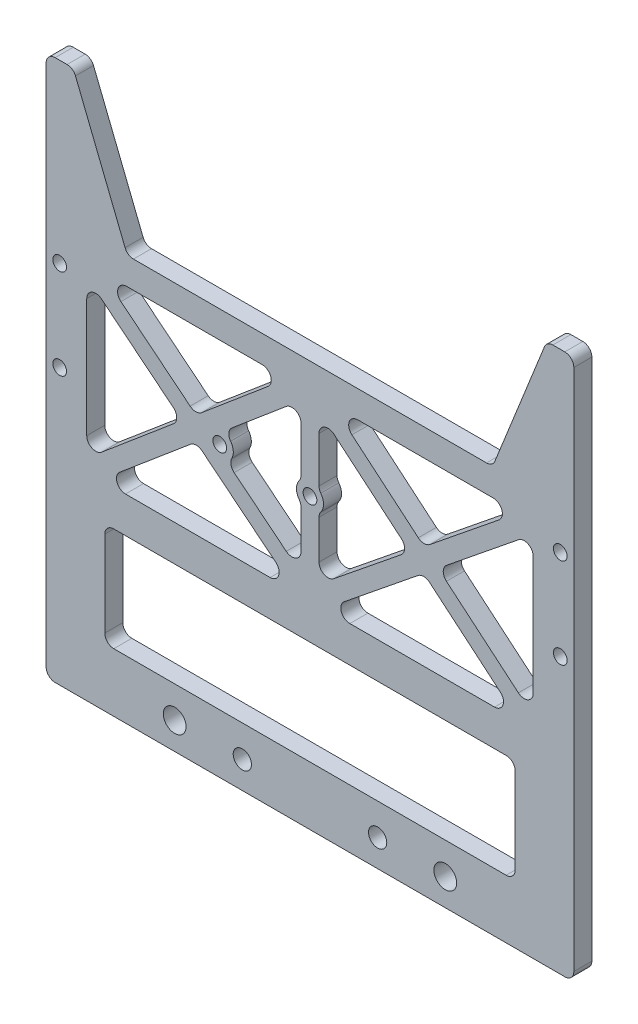
SolidWorks part; units mm, degrees
material "Thornel Mat VMA"
ref_plane "前视基准面" through (0, 0, 0) normal (0, 0, 1) x (1, 0, 0)
ref_plane "上视基准面" through (0, 0, 0) normal (0, 1, 0) x (1, 0, 0)
ref_plane "右视基准面" through (0, 0, 0) normal (1, 0, 0) x (0, 0, -1)
other "Configuration Table"
sketch "草图1" plane through (0, 0, 0) normal (0, 0, 1) x (1, 0, 0)
  line L1 (-58.5, -60) -> (58.5, -60)
  line L2 (-58.5, -60) -> (-58.5, 60)
  line L3 (-58.5, 60) -> (58.5, 60)
  line L4 (58.5, -60) -> (58.5, 60)
  line L5 (-58.5, -60) -> (58.5, 60) construction
  line L6 (-58.5, 60) -> (58.5, -60) construction
  point P0 (0, 0)
  dimension "D1" = 117
  dimension "D2" = 120
extrude "凸台-拉伸1" add sketch "草图1" along normal blind 4
sketch "草图2" [suppressed] plane through (0, 0, 4) normal (0, 0, 1) x (1, 0, 0)
  line L0 (-43.5, 60) -> (-28.5, 35)
  line L1 (58.5, 60) -> (-58.5, 60) construction
  line L2 (-28.5, 35) -> (28.5, 35)
  line L3 (28.5, 35) -> (43.5, 60)
  line L4 (43.5, 60) -> (-43.5, 60)
  line L5 (0, 60) -> (0, 35) construction
  line L6 (0, 35) -> (0, 0) construction
  line L7 (58.5, -60) -> (58.5, 60) construction
  dimension "D1" = 15
  dimension "D2" = 25
  dimension "D3" = 30
extrude "切除-拉伸1" [suppressed] cut sketch "草图2" against normal blind 10
sketch "草图3" [suppressed] plane through (0, 0, 4) normal (0, 0, 1) x (1, 0, 0)
  line L0 (48.5, -48) -> (48.5, -16.5) construction
  line L1 (-48.5, -16.5) -> (-48.5, -48) construction
  line L2 (48.5, -46) -> (48.5, -21)
  line L3 (-48.5, -21) -> (-48.5, -46)
  line L4 (48.5, -46) -> (-48.5, -46)
  line L5 (48.5, -21) -> (-48.5, -21)
  line L6 (-58.5, -60) -> (58.5, -60) construction
  dimension "D1" = 14
  dimension "D2" = 25
extrude "切除-拉伸2" [suppressed] cut sketch "草图3" against normal blind 10
sketch "草图4" plane through (0, 0, 0) normal (0, 0, -1) x (-1, 0, 0)
  line L0 (45.5, -47) -> (45.5, -24)
  line L1 (45.5, -24) -> (-45.5, -24)
  line L2 (-45.5, -24) -> (-45.5, -47)
  line L3 (-45.5, -47) -> (45.5, -47)
  line L4 (43.5, -45) -> (43.5, -26)
  line L5 (43.5, -26) -> (-43.5, -26)
  line L6 (-43.5, -26) -> (-43.5, -45)
  line L7 (-43.5, -45) -> (43.5, -45)
  line L8 (43.5, -45) -> (43.5, -26) construction
  line L9 (43.5, -26) -> (-43.5, -26) construction
  line L10 (-43.5, -26) -> (-43.5, -45) construction
  line L11 (-43.5, -45) -> (43.5, -45) construction
  dimension "D1" = 0
  dimension "D2" = 2
extrude "切除-拉伸3" cut sketch "草图4" against normal blind 10
sketch "草图5" plane through (0, 0, 4) normal (0, 0, 1) x (1, 0, 0)
  line L0 (-52.5, 60) -> (-40.5, 30)
  line L1 (58.5, 60) -> (-58.5, 60) construction
  line L2 (-40.5, 30) -> (40.5, 30)
  line L3 (40.5, 30) -> (52.5, 60)
  line L4 (52.5, 60) -> (-52.5, 60)
  line L5 (0, 60) -> (0, 30) construction
  line L6 (0, 30) -> (0, 0) construction
  line L7 (58.5, -60) -> (58.5, 60) construction
  dimension "D1" = 6
  dimension "D2" = 30
  dimension "D3" = 18
extrude "切除-拉伸4" cut sketch "草图5" against normal blind 10
sketch "草图6" plane through (0, 0, 0) normal (0, 0, -1) x (-1, 0, 0)
  circle A0 centre (-55.5, 1) radius 1.25 construction
  circle A1 centre (-55.5, 21) radius 1.25 construction
  circle A2 centre (-55.5, 1) radius 1.25 construction
  circle A3 centre (-55.5, 21) radius 1.25 construction
  circle A4 centre (-55.5, 21) radius 1.525
  circle A5 centre (-55.5, 1) radius 1.525
  dimension "D1" = 3.05
extrude "切除-拉伸5" cut sketch "草图6" against normal up to surface (4 mm away) up to face at (0, -35.5, 4)
mirror "镜向1" about plane through (0, 0, 0) normal (1, 0, 0) of "切除-拉伸5"
sketch "草图7" [suppressed] plane through (0, 0, 4) normal (0, 0, 1) x (1, 0, 0)
  circle A0 centre (-55.5, 2) radius 1.25 construction
  circle A1 centre (-55.5, 22) radius 1.25 construction
  circle A2 centre (-55.5, 2) radius 1.25 construction
  circle A3 centre (-55.5, 22) radius 1.25 construction
  circle A4 centre (-55.5, 22) radius 1.525
  circle A5 centre (-55.5, 2) radius 1.525
  dimension "D1" = 3.05
extrude "切除-拉伸6" [suppressed] cut sketch "草图7" against normal up to surface (4 mm away)
mirror "镜向2" [suppressed] about plane through (0, 0, 0) normal (1, 0, 0)
sketch "草图8" plane through (0, 0, 0) normal (0, 0, -1) x (-1, 0, 0)
  circle A0 centre (30, -54) radius 2 construction
  circle A1 centre (-30, -54) radius 2 construction
  circle A2 centre (30, -54) radius 2 construction
  circle A3 centre (-30, -54) radius 2 construction
  circle A4 centre (30, -54) radius 2.525
  circle A5 centre (-30, -54) radius 2.525
  dimension "D1" = 5.05
extrude "切除-拉伸7" cut sketch "草图8" against normal blind 40
fillet "圆角1" radius 2 12 edges at (58.5, 60, 2) (58.5, -60, 2) (-58.5, -60, 2) (-58.5, 60, 2) (-52.5, 60, 2) (-40.5, 30, 2) (40.5, 30, 2) (52.5, 60, 2) (-45.5, -24, 2) (-45.5, -47, 2) (45.5, -47, 2) (45.5, -24, 2)
fillet "圆角2" [suppressed] radius 3
sketch "草图9" [suppressed] plane through (0, 0, 0) normal (0, 0, -1) x (-1, 0, 0)
  line L0 (-26.8014, 35) -> (26.8014, 35) construction
  line L1 (-50.5, -13) -> (50.5, -13)
  line L2 (-50.5, -13) -> (-50.5, 29)
  line L3 (-50.5, 29) -> (50.5, 29)
  line L4 (50.5, -13) -> (50.5, 29)
  line L5 (-50.5, -13) -> (50.5, 29) construction
  line L6 (-50.5, 29) -> (50.5, -13) construction
  line L7 (45.5, -21) -> (-45.5, -21) construction
  line L8 (0, 8) -> (0, 0) construction
  line L9 (-51.2679, 27.1533) -> (49.7321, -14.8467)
  line L10 (-49.7321, -14.8467) -> (51.2679, 27.1533)
  line L11 (-49.7321, 30.8467) -> (51.2679, -11.1533)
  line L12 (-51.2679, -11.1533) -> (49.7321, 30.8467)
  line L13 (-51.2679, 27.1533) -> (-49.7321, 30.8467)
  line L14 (49.7321, -14.8467) -> (51.2679, -11.1533)
  line L15 (-49.7321, -14.8467) -> (-51.2679, -11.1533)
  line L16 (51.2679, 27.1533) -> (49.7321, 30.8467)
  circle A0 centre (55.5, 2) radius 1.525 construction
  point P0 (0, 8)
  dimension "D1" = 6
  dimension "D2" = 8
  dimension "D3" = 5
  dimension "D4" = 2
  dimension "D5" = 2
extrude "切除-拉伸8" [suppressed] cut sketch "草图9" against normal blind 78 contours L2 L12 L9 | L10 L1 L9 | L10 L11 L4 | L11 L12 L3
sketch "草图10" [suppressed] plane through (0, 0, 0) normal (0, 0, -1) x (-1, 0, 0)
  line L0 (0, 29) -> (0, -13) construction
  line L1 (-45.2912, 29) -> (45.2912, 29) construction
  line L2 (-45.2912, -13) -> (45.2912, -13) construction
  line L3 (-2, 29) -> (-2, -13)
  line L4 (2, 29) -> (2, -13)
  line L5 (-2, 29) -> (2, 29)
  line L6 (-2, -13) -> (2, -13)
  line L7 (-27.8544, 17.417) -> (-27.8544, -1.417)
  line L8 (-50.5, 26.834) -> (-5.2088, 8) construction
  line L9 (-50.5, -10.834) -> (-5.2088, 8) construction
  line L10 (-27.8544, 17.417) -> (-31.8544, 19.0804)
  line L11 (-31.8544, 19.0804) -> (-31.8544, -3.0804)
  line L12 (-31.8544, -3.0804) -> (-27.8544, -1.417)
  line L13 (27.8544, 17.417) -> (31.8544, 19.0804)
  line L14 (31.8544, 19.0804) -> (31.8544, -3.0804)
  line L15 (31.8544, -3.0804) -> (27.8544, -1.417)
  line L16 (27.8544, 17.417) -> (27.8544, -1.417)
  dimension "D3" = 4
  dimension "D1" = 2
  dimension "D2" = 2
extrude "凸台-拉伸2" [suppressed] add sketch "草图10" against normal up to surface (4 mm away)
sketch "草图11" [suppressed] plane through (0, 0, 4) normal (0, 0, 1) x (1, 0, 0)
  line L0 (46.331, 55) -> (33.731, 34)
  line L1 (33.731, 34) -> (52.5, 34)
  line L2 (52.5, 34) -> (52.5, 55)
  line L3 (52.5, 55) -> (46.331, 55)
  line L4 (58.5, -57) -> (58.5, 57) construction
  line L5 (55.5, 60) -> (45.1986, 60) construction
  line L6 (29.3739, 36.4565) -> (42.6261, 58.5435) construction
  line L7 (45.2912, 29) -> (2, 29) construction
  line L8 (0, 0) -> (0, 61.4622) construction
  line L9 (-52.5, 34) -> (-52.5, 55)
  line L10 (-33.731, 34) -> (-52.5, 34)
  line L11 (-46.331, 55) -> (-33.731, 34)
  line L12 (-52.5, 55) -> (-46.331, 55)
  dimension "D1" = 6
  dimension "D2" = 5
  dimension "D3" = 5
  dimension "D4" = 5
extrude "切除-拉伸9" [suppressed] cut sketch "草图11" against normal up to surface (4 mm away)
fillet "圆角3" [suppressed] radius 1.5
sketch "草图12" plane through (0, 0, 0) normal (0, 0, -1) x (-1, 0, 0)
  line L0 (43.5, -24) -> (-43.5, -24) construction
  line L1 (-49.5, -16) -> (49.5, -16)
  line L2 (-49.5, -16) -> (-49.5, 24)
  line L3 (-49.5, 24) -> (49.5, 24)
  line L4 (49.5, -16) -> (49.5, 24)
  line L5 (-39.1459, 30) -> (39.1459, 30) construction
  line L6 (-49.5, 24) -> (0, -16) construction
  line L7 (0, -16) -> (49.5, 24) construction
  line L8 (0, 24) -> (0, -16) construction
  line L9 (-50.757, 22.4444) -> (-1.257, -17.5556)
  line L10 (-2, 24) -> (-2, -16)
  line L11 (1.257, -17.5556) -> (50.757, 22.4444)
  line L12 (-48.243, 25.5556) -> (1.257, -14.4444)
  line L13 (2, 24) -> (2, -16)
  line L14 (-1.257, -14.4444) -> (48.243, 25.5556)
  circle A0 centre (55.5, 21) radius 1.525 construction
  circle A1 centre (-55.5, 21) radius 1.525 construction
  dimension "D1" = 6
  dimension "D2" = 6
  dimension "D3" = 8
  dimension "D4" = 6
  dimension "D5" = 2
  dimension "D6" = 2
extrude "切除-拉伸10" cut sketch "草图12" against normal up to surface (4 mm away) contours L11 L1 L4 | L13 L14 L3 | L3 L12 L10 | L9 L2 L1 up to face at (-32.525, -54, 4)
sketch "草图15" plane through (0, 0, 4) normal (0, 0, 1) x (1, 0, 0)
  line L0 (-2, 24) -> (-49.5, -16) construction
  line L1 (2, 24) -> (49.5, -16) construction
  line L2 (-3.2883, 25.5298) -> (-50.7883, -14.4702)
  line L3 (0.7117, 22.4702) -> (48.2117, -17.5298)
  line L4 (-0.7117, 22.4702) -> (-48.2117, -17.5298)
  line L5 (3.2883, 25.5298) -> (50.7883, -14.4702)
  line L6 (-3.2883, 25.5298) -> (-0.7117, 22.4702)
  line L7 (-50.7883, -14.4702) -> (-48.2117, -17.5298)
  line L8 (0.7117, 22.4702) -> (3.2883, 25.5298)
  line L9 (48.2117, -17.5298) -> (50.7883, -14.4702)
  dimension "D1" = 2
  dimension "D2" = 2
extrude "凸台-拉伸4" add sketch "草图15" against normal up to surface (4 mm away) up to face at (-16.7726, 12.0625, 0)
fillet "圆角4" radius 2 24 edges at (-46.3951, -16, 2) (-3.1821, -16, 2) (-25.2341, 1.8198, 2) (-22.1176, 4.4442, 2) (-2, -11.8125, 2) (-2, 21.3853, 2) (-5.1049, 24, 2) (-46.3179, 24, 2) (-25.2866, 7.005, 2) (-28.403, 4.3806, 2) (-49.5, 21.4286, 2) (-49.5, -13.3853, 2) (49.5, -13.3853, 2) (49.5, 21.4286, 2) (28.403, 4.3806, 2) (25.2866, 7.005, 2) (46.3179, 24, 2) (5.1049, 24, 2) (2, 21.3853, 2) (2, -11.8125, 2) (22.1176, 4.4442, 2) (3.1821, -16, 2) (25.2341, 1.8198, 2) (46.3951, -16, 2)
sketch "草图16" [suppressed] plane through (0, 0, 4) normal (0, 0, 1) x (1, 0, 0)
  circle A0 centre (5, 4) radius 1.25 construction
  circle A1 centre (-15, 4) radius 1.25 construction
  circle A2 centre (5, 4) radius 1.25 construction
  circle A3 centre (-15, 4) radius 1.25 construction
  circle A4 centre (-15, 4) radius 3
  circle A5 centre (5, 4) radius 3
  dimension "D1" = 6
extrude "凸台-拉伸5" [suppressed] add sketch "草图16" against normal up to surface (4 mm away)
sketch "草图17" [suppressed] plane through (0, 0, 0) normal (0, 0, -1) x (-1, 0, 0)
  circle A0 centre (-5, 4) radius 1.525
  circle A1 centre (15, 4) radius 1.525
  dimension "D1" = 3.05
extrude "切除-拉伸11" [suppressed] cut sketch "草图17" against normal up to surface (4 mm away)
fillet "圆角5" [suppressed] radius 2
sketch "草图18" plane through (0, 0, 0) normal (0, 0, -1) x (-1, 0, 0)
  circle A0 centre (20, 4) radius 1.25 construction
  circle A1 centre (0, 4) radius 1.25 construction
  circle A2 centre (20, 4) radius 1.25 construction
  circle A3 centre (0, 4) radius 1.25 construction
  circle A4 centre (20, 4) radius 3
  dimension "D1" = 6
extrude "凸台-拉伸6" add sketch "草图18" against normal up to surface (4 mm away) up to face at (24.9948, -9.3021, 4)
sketch "草图19" plane through (0, 0, 4) normal (0, 0, 1) x (1, 0, 0)
  circle A0 centre (0, 4) radius 1.525
  circle A1 centre (-20, 4) radius 1.525
  dimension "D1" = 3.05
extrude "切除-拉伸12" cut sketch "草图19" against normal up to surface (4 mm away) up to face at (-8.2351, 4.5874, 0)
sketch "草图20" plane through (0, 0, 0) normal (0, 0, -1) x (-1, 0, 0)
  circle A0 centre (0, 4) radius 3
  circle A1 centre (0, 4) radius 1.525 construction
  circle A2 centre (0, 4) radius 1.525
  dimension "D1" = 6
extrude "凸台-拉伸7" add sketch "草图20" against normal up to surface (4 mm away) up to face at (1.525, 4, 4)
fillet "圆角6" radius 2 6 edges at (-2, 6.2361, 2) (-2, 1.7639, 2) (2, 1.7639, 2) (2, 6.2361, 2) (-19.2087, 6.8938, 2) (-18.4155, 1.4526, 2)
sketch "草图21" plane through (0, 0, 4) normal (0, 0, 1) x (1, 0, 0)
  line L0 (-30, -54) -> (30, -54) construction
  line L1 (0, -54) -> (0, -60) construction
  line L2 (-56.5, -60) -> (56.5, -60) construction
  circle A0 centre (-15, -54) radius 2.025
  circle A1 centre (15, -54) radius 2.025
  dimension "D1" = 4.05
  dimension "D2" = 30
extrude "切除-拉伸13" cut sketch "草图21" against normal blind 10
